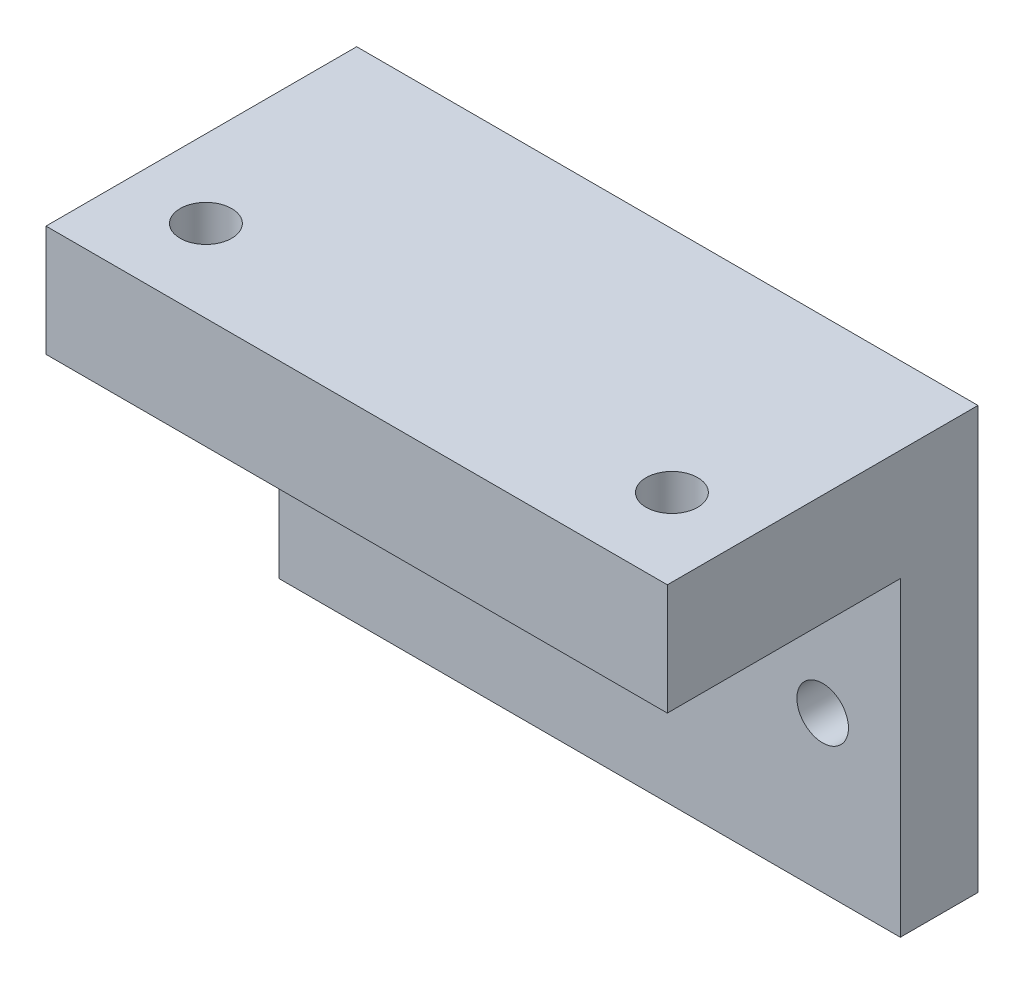
SolidWorks part; units mm, degrees
ref_plane "前视基准面" through (0, 0, 0) normal (0, 0, 1) x (1, 0, 0)
ref_plane "上视基准面" through (0, 0, 0) normal (0, 1, 0) x (1, 0, 0)
ref_plane "右视基准面" through (0, 0, 0) normal (1, 0, 0) x (0, 0, -1)
sketch "草图1" plane through (0, 0, 0) normal (0, 0, 1) x (1, 0, 0)
  line L1 (-40, -20) -> (40, -20)
  line L2 (-40, -20) -> (-40, 20)
  line L3 (-40, 20) -> (40, 20)
  line L4 (40, -20) -> (40, 20)
  line L5 (-40, -20) -> (40, 20) construction
  line L6 (-40, 20) -> (40, -20) construction
  point P0 (0, 0)
  dimension "D1" = 80
  dimension "D2" = 40
extrude "凸台-拉伸1" add sketch "草图1" along normal blind 10
sketch "草图2" plane through (0, 0, 0) normal (0, 0, -1) x (-1, 0, 0)
  line L0 (40, 20) -> (40, -20) construction
  line L1 (-40, 20) -> (40, 20)
  line L2 (-40, 20) -> (-40, 34.3064)
  line L3 (-40, 34.3064) -> (40, 34.3064)
  line L4 (40, 20) -> (40, 34.3064)
  point P7 (40, 28.888)
sketch "草图4" plane through (0, 0, 10) normal (0, 0, 1) x (1, 0, 0)
  circle A0 centre (30, 0) radius 3.32
  circle A1 centre (-30, 0) radius 3.32
  dimension "D1" = 6.64
  dimension "D4" = 6.64
  dimension "D2" = 30
  dimension "D3" = 30
extrude "切除-拉伸3" cut sketch "草图4" against normal through all
extrude "凸台-拉伸3" add sketch "草图2" against normal blind 40 contours L3 L4 L1 L2
sketch "草图5" plane through (0, 20, 0) normal (0, -1, 0) x (1, 0, 0)
  line L0 (-40, 40) -> (-40, 10) construction
  line L1 (40, 40) -> (40, 10) construction
  circle A0 centre (30, 29.4091) radius 3.32
  circle A1 centre (-30, 29.4091) radius 3.32
  dimension "D3" = 6.64
  dimension "D4" = 6.64
  dimension "D1" = 10
  dimension "D2" = 10
extrude "切除-拉伸4" cut sketch "草图5" against normal blind 40
